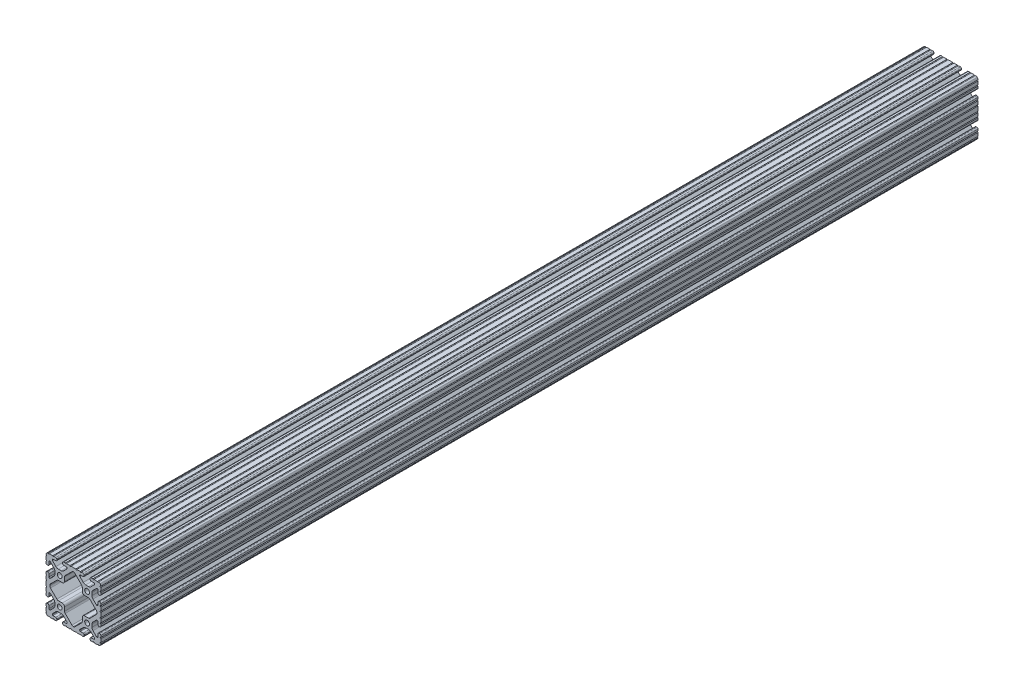
SolidWorks part; units mm, degrees
material "6061-T6 (SS)"
ref_plane "Front Plane" through (0, 0, 0) normal (0, 0, 1) x (1, 0, 0)
ref_plane "Top Plane" through (0, 0, 0) normal (0, 1, 0) x (1, 0, 0)
ref_plane "Right Plane" through (0, 0, 0) normal (1, 0, 0) x (0, 0, -1)
ref_plane "Plane1" through (0, 0, -609.6) normal (0, 0, -1) x (-1, 0, 0)
sketch "Sketch1" plane through (0, 0, -609.6) normal (0, 0, -1) x (-1, 0, 0)
  line L0 (31.9021, -2.4756) -> (23.0141, -11.3637)
  line L1 (20.769, -12.2936) -> (15.4686, -12.2936)
  line L2 (12.2936, -15.4686) -> (12.2936, -20.5983)
  line L3 (11.3637, -22.8433) -> (2.0515, -32.1555)
  line L4 (-2.0515, -32.1555) -> (-11.3637, -22.8433)
  line L5 (-12.2936, -20.5983) -> (-12.2936, -15.4686)
  line L6 (-15.4686, -12.2936) -> (-20.769, -12.2936)
  line L7 (-23.0141, -11.3637) -> (-31.9021, -2.4756)
  line L8 (-31.9021, 2.4756) -> (-23.0141, 11.3637)
  line L9 (-20.769, 12.2936) -> (-15.4686, 12.2936)
  line L10 (-12.2936, 15.4686) -> (-12.2936, 20.5983)
  line L11 (-11.3637, 22.8433) -> (-2.0515, 32.1555)
  line L12 (2.0515, 32.1555) -> (11.3637, 22.8433)
  line L13 (12.2936, 20.5983) -> (12.2936, 15.4686)
  line L14 (15.4686, 12.2936) -> (20.769, 12.2936)
  line L15 (23.0141, 11.3637) -> (31.9021, 2.4756)
  line L16 (36.5252, -23.0554) -> (35.6108, -23.0554)
  line L17 (34.036, -24.6302) -> (34.036, -28.448)
  line L18 (33.147, -29.337) -> (32.6643, -29.337)
  line L19 (32.0357, -29.0766) -> (27.1976, -24.2385)
  line L20 (25.8064, -20.8799) -> (25.8064, -17.2201)
  line L21 (27.1976, -13.8615) -> (31.9489, -9.1101)
  line L22 (32.7869, -8.763) -> (33.0603, -8.763)
  line L23 (34.036, -9.7387) -> (34.036, -13.4698)
  line L24 (35.6108, -15.0446) -> (36.5252, -15.0446)
  line L25 (38.1, -13.4698) -> (38.1, -11.075)
  line L26 (38.1, -9.552) -> (38.1, -4.7238)
  line L27 (38.1, -3.2007) -> (38.1, 3.2007)
  line L28 (38.1, 4.7238) -> (38.1, 9.552)
  line L29 (38.1, 11.075) -> (38.1, 13.4698)
  line L30 (36.5252, 15.0446) -> (35.6108, 15.0446)
  line L31 (34.036, 13.4698) -> (34.036, 9.7387)
  line L32 (33.0603, 8.763) -> (32.7869, 8.763)
  line L33 (31.9489, 9.1101) -> (27.1976, 13.8615)
  line L34 (25.8064, 17.2201) -> (25.8064, 20.8799)
  line L35 (27.1976, 24.2385) -> (32.0357, 29.0766)
  line L36 (32.6643, 29.337) -> (33.147, 29.337)
  line L37 (34.036, 28.448) -> (34.036, 24.6302)
  line L38 (35.6108, 23.0554) -> (36.5252, 23.0554)
  line L39 (38.1, 24.6302) -> (38.1, 27.0238)
  line L40 (38.1, 28.5453) -> (38.1, 33.373)
  line L41 (33.4288, 38.1) -> (28.6011, 38.1)
  line L42 (27.0772, 38.1) -> (24.6888, 38.1)
  line L43 (23.114, 36.5252) -> (23.114, 35.6108)
  line L44 (24.6888, 34.036) -> (28.448, 34.036)
  line L45 (29.337, 33.147) -> (29.337, 32.7207)
  line L46 (29.1002, 31.8885) -> (24.4093, 27.1976)
  line L47 (21.0507, 25.8064) -> (17.0493, 25.8064)
  line L48 (13.6907, 27.1976) -> (9.0234, 31.8649)
  line L49 (8.763, 32.4935) -> (8.763, 33.147)
  line L50 (9.652, 34.036) -> (13.4112, 34.036)
  line L51 (14.986, 35.6108) -> (14.986, 36.5252)
  line L52 (13.4112, 38.1) -> (11.1289, 38.1)
  line L53 (9.6053, 38.1) -> (4.7773, 38.1)
  line L54 (3.2537, 38.1) -> (-3.2537, 38.1)
  line L55 (-4.7773, 38.1) -> (-9.6053, 38.1)
  line L56 (-11.1289, 38.1) -> (-13.4112, 38.1)
  line L57 (-14.986, 36.5252) -> (-14.986, 35.6108)
  line L58 (-13.4112, 34.036) -> (-9.652, 34.036)
  line L59 (-8.763, 33.147) -> (-8.763, 32.4935)
  line L60 (-9.0234, 31.8649) -> (-13.6907, 27.1976)
  line L61 (-17.0493, 25.8064) -> (-21.0507, 25.8064)
  line L62 (-24.4093, 27.1976) -> (-29.1002, 31.8885)
  line L63 (-29.337, 32.7207) -> (-29.337, 33.147)
  line L64 (-28.448, 34.036) -> (-24.6888, 34.036)
  line L65 (-23.114, 35.6108) -> (-23.114, 36.5252)
  line L66 (-24.6888, 38.1) -> (-27.0772, 38.1)
  line L67 (-28.6011, 38.1) -> (-33.4288, 38.1)
  line L68 (-38.1, 33.373) -> (-38.1, 28.5453)
  line L69 (-38.1, 27.0238) -> (-38.1, 24.6302)
  line L70 (-36.5252, 23.0554) -> (-35.6108, 23.0554)
  line L71 (-34.036, 24.6302) -> (-34.036, 28.448)
  line L72 (-33.147, 29.337) -> (-32.6643, 29.337)
  line L73 (-32.0357, 29.0766) -> (-27.1976, 24.2385)
  line L74 (-25.8064, 20.8799) -> (-25.8064, 17.2201)
  line L75 (-27.1976, 13.8615) -> (-31.9489, 9.1101)
  line L76 (-32.7869, 8.763) -> (-33.0603, 8.763)
  line L77 (-34.036, 9.7387) -> (-34.036, 13.4698)
  line L78 (-35.6108, 15.0446) -> (-36.5252, 15.0446)
  line L79 (-38.1, 13.4698) -> (-38.1, 11.075)
  line L80 (-38.1, 9.552) -> (-38.1, 4.7238)
  line L81 (-38.1, 3.2007) -> (-38.1, -3.2007)
  line L82 (-38.1, -4.7238) -> (-38.1, -9.552)
  line L83 (-38.1, -11.075) -> (-38.1, -13.4698)
  line L84 (-36.5252, -15.0446) -> (-35.6108, -15.0446)
  line L85 (-34.036, -13.4698) -> (-34.036, -9.7387)
  line L86 (-33.0603, -8.763) -> (-32.7869, -8.763)
  line L87 (-31.9489, -9.1101) -> (-27.1976, -13.8615)
  line L88 (-25.8064, -17.2201) -> (-25.8064, -20.8799)
  line L89 (-27.1976, -24.2385) -> (-32.0357, -29.0766)
  line L90 (-32.6643, -29.337) -> (-33.147, -29.337)
  line L91 (-34.036, -28.448) -> (-34.036, -24.6302)
  line L92 (-35.6108, -23.0554) -> (-36.5252, -23.0554)
  line L93 (-38.1, -24.6302) -> (-38.1, -27.0238)
  line L94 (-38.1, -28.5453) -> (-38.1, -33.373)
  line L95 (-33.4288, -38.1) -> (-28.6011, -38.1)
  line L96 (-27.0772, -38.1) -> (-24.6888, -38.1)
  line L97 (-23.114, -36.5252) -> (-23.114, -35.6108)
  line L98 (-24.6888, -34.036) -> (-28.448, -34.036)
  line L99 (-29.337, -33.147) -> (-29.337, -32.7207)
  line L100 (-29.1002, -31.8885) -> (-24.4093, -27.1976)
  line L101 (-21.0507, -25.8064) -> (-17.0493, -25.8064)
  line L102 (-13.6907, -27.1976) -> (-9.0234, -31.8649)
  line L103 (-8.763, -32.4935) -> (-8.763, -33.147)
  line L104 (-9.652, -34.036) -> (-13.4112, -34.036)
  line L105 (-14.986, -35.6108) -> (-14.986, -36.5252)
  line L106 (-13.4112, -38.1) -> (-11.1289, -38.1)
  line L107 (-9.6053, -38.1) -> (-4.7773, -38.1)
  line L108 (-3.2537, -38.1) -> (3.2537, -38.1)
  line L109 (4.7773, -38.1) -> (9.6053, -38.1)
  line L110 (11.1289, -38.1) -> (13.4112, -38.1)
  line L111 (14.986, -36.5252) -> (14.986, -35.6108)
  line L112 (13.4112, -34.036) -> (9.652, -34.036)
  line L113 (8.763, -33.147) -> (8.763, -32.4935)
  line L114 (9.0234, -31.8649) -> (13.6907, -27.1976)
  line L115 (17.0493, -25.8064) -> (21.0507, -25.8064)
  line L116 (24.4093, -27.1976) -> (29.1002, -31.8885)
  line L117 (29.337, -32.7207) -> (29.337, -33.147)
  line L118 (28.448, -34.036) -> (24.6888, -34.036)
  line L119 (23.114, -35.6108) -> (23.114, -36.5252)
  line L120 (24.6888, -38.1) -> (27.0772, -38.1)
  line L121 (28.6011, -38.1) -> (33.4288, -38.1)
  line L122 (38.1, -33.373) -> (38.1, -28.5453)
  line L123 (38.1, -27.0238) -> (38.1, -24.6302)
  arc A0 (31.9021, 2.4756) -> (32.7287, 0) centre (29.8367, 0.4102) cw
  arc A1 (32.7287, 0) -> (31.9021, -2.4756) centre (29.8367, -0.4102) cw
  arc A2 (23.0141, -11.3637) -> (20.769, -12.2936) centre (20.769, -9.1186) cw
  arc A3 (15.4686, -12.2936) -> (12.2936, -15.4686) centre (15.4686, -15.4686) ccw
  arc A4 (12.2936, -20.5983) -> (11.3637, -22.8433) centre (9.1186, -20.5983) cw
  arc A5 (2.0515, -32.1555) -> (0, -33.011) centre (-0.0139, -30.09) cw
  arc A6 (0, -33.011) -> (-2.0515, -32.1555) centre (0.0139, -30.09) cw
  arc A7 (-11.3637, -22.8433) -> (-12.2936, -20.5983) centre (-9.1186, -20.5983) cw
  arc A8 (-12.2936, -15.4686) -> (-15.4686, -12.2936) centre (-15.4686, -15.4686) ccw
  arc A9 (-20.769, -12.2936) -> (-23.0141, -11.3637) centre (-20.769, -9.1186) cw
  arc A10 (-31.9021, -2.4756) -> (-32.7287, 0) centre (-29.8367, -0.4102) cw
  arc A11 (-32.7287, 0) -> (-31.9021, 2.4756) centre (-29.8367, 0.4102) cw
  arc A12 (-23.0141, 11.3637) -> (-20.769, 12.2936) centre (-20.769, 9.1186) cw
  arc A13 (-15.4686, 12.2936) -> (-12.2936, 15.4686) centre (-15.4686, 15.4686) ccw
  arc A14 (-12.2936, 20.5983) -> (-11.3637, 22.8433) centre (-9.1186, 20.5983) cw
  arc A15 (-2.0515, 32.1555) -> (0, 33.011) centre (0.0139, 30.09) cw
  arc A16 (0, 33.011) -> (2.0515, 32.1555) centre (-0.0139, 30.09) cw
  arc A17 (11.3637, 22.8433) -> (12.2936, 20.5983) centre (9.1186, 20.5983) cw
  arc A18 (12.2936, 15.4686) -> (15.4686, 12.2936) centre (15.4686, 15.4686) ccw
  arc A19 (20.769, 12.2936) -> (23.0141, 11.3637) centre (20.769, 9.1186) cw
  circle A20 centre (19.05, -19.05) radius 3.3274
  circle A21 centre (19.05, 19.05) radius 3.3274
  circle A22 centre (-19.05, 19.05) radius 3.3274
  circle A23 centre (-19.05, -19.05) radius 3.3274
  arc A24 (38.1, -24.6302) -> (36.5252, -23.0554) centre (36.5252, -24.6302) ccw
  arc A25 (35.6108, -23.0554) -> (34.036, -24.6302) centre (35.6108, -24.6302) ccw
  arc A26 (34.036, -28.448) -> (33.147, -29.337) centre (33.147, -28.448) cw
  arc A27 (32.6643, -29.337) -> (32.0357, -29.0766) centre (32.6643, -28.448) cw
  arc A28 (27.1976, -24.2385) -> (25.8064, -20.8799) centre (30.5562, -20.8799) cw
  arc A29 (25.8064, -17.2201) -> (27.1976, -13.8615) centre (30.5562, -17.2201) cw
  arc A30 (31.9489, -9.1101) -> (32.7869, -8.763) centre (32.7869, -9.9481) cw
  arc A31 (33.0603, -8.763) -> (34.036, -9.7387) centre (33.0603, -9.7387) cw
  arc A32 (34.036, -13.4698) -> (35.6108, -15.0446) centre (35.6108, -13.4698) ccw
  arc A33 (36.5252, -15.0446) -> (38.1, -13.4698) centre (36.5252, -13.4698) ccw
  arc A34 (38.1, -11.075) -> (38.1, -9.552) centre (37.9035, -10.3135) cw
  arc A35 (38.1, -4.7238) -> (38.1, -3.2007) centre (37.9035, -3.9622) cw
  arc A36 (38.1, 3.2007) -> (38.1, 4.7238) centre (37.9035, 3.9622) cw
  arc A37 (38.1, 9.552) -> (38.1, 11.075) centre (37.9035, 10.3135) cw
  arc A38 (38.1, 13.4698) -> (36.5252, 15.0446) centre (36.5252, 13.4698) ccw
  arc A39 (35.6108, 15.0446) -> (34.036, 13.4698) centre (35.6108, 13.4698) ccw
  arc A40 (34.036, 9.7387) -> (33.0603, 8.763) centre (33.0603, 9.7387) cw
  arc A41 (32.7869, 8.763) -> (31.9489, 9.1101) centre (32.7869, 9.9481) cw
  arc A42 (27.1976, 13.8615) -> (25.8064, 17.2201) centre (30.5562, 17.2201) cw
  arc A43 (25.8064, 20.8799) -> (27.1976, 24.2385) centre (30.5562, 20.8799) cw
  arc A44 (32.0357, 29.0766) -> (32.6643, 29.337) centre (32.6643, 28.448) cw
  arc A45 (33.147, 29.337) -> (34.036, 28.448) centre (33.147, 28.448) cw
  arc A46 (34.036, 24.6302) -> (35.6108, 23.0554) centre (35.6108, 24.6302) ccw
  arc A47 (36.5252, 23.0554) -> (38.1, 24.6302) centre (36.5252, 24.6302) ccw
  arc A48 (38.1, 27.0238) -> (38.1, 28.5453) centre (37.9035, 27.7845) cw
  arc A49 (38.1, 33.373) -> (38.1, 34.8455) centre (37.9035, 34.1092) cw
  arc A50 (38.1, 34.8455) -> (37.0861, 37.1826) centre (34.925, 34.8566) ccw
  arc A51 (37.0861, 37.1826) -> (34.9527, 38.1) centre (34.8521, 34.9266) ccw
  arc A52 (34.9527, 38.1) -> (33.4288, 38.1) centre (34.1907, 38.0824) cw
  arc A53 (28.6011, 38.1) -> (27.0772, 38.1) centre (27.8392, 38.0824) cw
  arc A54 (24.6888, 38.1) -> (23.114, 36.5252) centre (24.6888, 36.5252) ccw
  arc A55 (23.114, 35.6108) -> (24.6888, 34.036) centre (24.6888, 35.6108) ccw
  arc A56 (28.448, 34.036) -> (29.337, 33.147) centre (28.448, 33.147) cw
  arc A57 (29.337, 32.7207) -> (29.1002, 31.8885) centre (28.4716, 32.5172) cw
  arc A58 (24.4093, 27.1976) -> (21.0507, 25.8064) centre (21.0507, 30.5562) cw
  arc A59 (17.0493, 25.8064) -> (13.6907, 27.1976) centre (17.0493, 30.5562) cw
  arc A60 (9.0234, 31.8649) -> (8.763, 32.4935) centre (9.652, 32.4935) cw
  arc A61 (8.763, 33.147) -> (9.652, 34.036) centre (9.652, 33.147) cw
  arc A62 (13.4112, 34.036) -> (14.986, 35.6108) centre (13.4112, 35.6108) ccw
  arc A63 (14.986, 36.5252) -> (13.4112, 38.1) centre (13.4112, 36.5252) ccw
  arc A64 (11.1289, 38.1) -> (9.6053, 38.1) centre (10.3671, 38.0824) cw
  arc A65 (4.7773, 38.1) -> (3.2537, 38.1) centre (4.0155, 38.0824) cw
  arc A66 (-3.2537, 38.1) -> (-4.7773, 38.1) centre (-4.0155, 38.0824) cw
  arc A67 (-9.6053, 38.1) -> (-11.1289, 38.1) centre (-10.3671, 38.0824) cw
  arc A68 (-13.4112, 38.1) -> (-14.986, 36.5252) centre (-13.4112, 36.5252) ccw
  arc A69 (-14.986, 35.6108) -> (-13.4112, 34.036) centre (-13.4112, 35.6108) ccw
  arc A70 (-9.652, 34.036) -> (-8.763, 33.147) centre (-9.652, 33.147) cw
  arc A71 (-8.763, 32.4935) -> (-9.0234, 31.8649) centre (-9.652, 32.4935) cw
  arc A72 (-13.6907, 27.1976) -> (-17.0493, 25.8064) centre (-17.0493, 30.5562) cw
  arc A73 (-21.0507, 25.8064) -> (-24.4093, 27.1976) centre (-21.0507, 30.5562) cw
  arc A74 (-29.1002, 31.8885) -> (-29.337, 32.7207) centre (-28.4716, 32.5172) cw
  arc A75 (-29.337, 33.147) -> (-28.448, 34.036) centre (-28.448, 33.147) cw
  arc A76 (-24.6888, 34.036) -> (-23.114, 35.6108) centre (-24.6888, 35.6108) ccw
  arc A77 (-23.114, 36.5252) -> (-24.6888, 38.1) centre (-24.6888, 36.5252) ccw
  arc A78 (-27.0772, 38.1) -> (-28.6011, 38.1) centre (-27.8392, 38.0824) cw
  arc A79 (-33.4288, 38.1) -> (-34.9527, 38.1) centre (-34.1907, 38.0824) cw
  arc A80 (-34.9527, 38.1) -> (-37.0861, 37.1826) centre (-34.8521, 34.9266) ccw
  arc A81 (-37.0861, 37.1826) -> (-38.1, 34.8455) centre (-34.925, 34.8566) ccw
  arc A82 (-38.1, 34.8455) -> (-38.1, 33.373) centre (-37.9035, 34.1092) cw
  arc A83 (-38.1, 28.5453) -> (-38.1, 27.0238) centre (-37.9035, 27.7845) cw
  arc A84 (-38.1, 24.6302) -> (-36.5252, 23.0554) centre (-36.5252, 24.6302) ccw
  arc A85 (-35.6108, 23.0554) -> (-34.036, 24.6302) centre (-35.6108, 24.6302) ccw
  arc A86 (-34.036, 28.448) -> (-33.147, 29.337) centre (-33.147, 28.448) cw
  arc A87 (-32.6643, 29.337) -> (-32.0357, 29.0766) centre (-32.6643, 28.448) cw
  arc A88 (-27.1976, 24.2385) -> (-25.8064, 20.8799) centre (-30.5562, 20.8799) cw
  arc A89 (-25.8064, 17.2201) -> (-27.1976, 13.8615) centre (-30.5562, 17.2201) cw
  arc A90 (-31.9489, 9.1101) -> (-32.7869, 8.763) centre (-32.7869, 9.9481) cw
  arc A91 (-33.0603, 8.763) -> (-34.036, 9.7387) centre (-33.0603, 9.7387) cw
  arc A92 (-34.036, 13.4698) -> (-35.6108, 15.0446) centre (-35.6108, 13.4698) ccw
  arc A93 (-36.5252, 15.0446) -> (-38.1, 13.4698) centre (-36.5252, 13.4698) ccw
  arc A94 (-38.1, 11.075) -> (-38.1, 9.552) centre (-37.9035, 10.3135) cw
  arc A95 (-38.1, 4.7238) -> (-38.1, 3.2007) centre (-37.9035, 3.9622) cw
  arc A96 (-38.1, -3.2007) -> (-38.1, -4.7238) centre (-37.9035, -3.9622) cw
  arc A97 (-38.1, -9.552) -> (-38.1, -11.075) centre (-37.9035, -10.3135) cw
  arc A98 (-38.1, -13.4698) -> (-36.5252, -15.0446) centre (-36.5252, -13.4698) ccw
  arc A99 (-35.6108, -15.0446) -> (-34.036, -13.4698) centre (-35.6108, -13.4698) ccw
  arc A100 (-34.036, -9.7387) -> (-33.0603, -8.763) centre (-33.0603, -9.7387) cw
  arc A101 (-32.7869, -8.763) -> (-31.9489, -9.1101) centre (-32.7869, -9.9481) cw
  arc A102 (-27.1976, -13.8615) -> (-25.8064, -17.2201) centre (-30.5562, -17.2201) cw
  arc A103 (-25.8064, -20.8799) -> (-27.1976, -24.2385) centre (-30.5562, -20.8799) cw
  arc A104 (-32.0357, -29.0766) -> (-32.6643, -29.337) centre (-32.6643, -28.448) cw
  arc A105 (-33.147, -29.337) -> (-34.036, -28.448) centre (-33.147, -28.448) cw
  arc A106 (-34.036, -24.6302) -> (-35.6108, -23.0554) centre (-35.6108, -24.6302) ccw
  arc A107 (-36.5252, -23.0554) -> (-38.1, -24.6302) centre (-36.5252, -24.6302) ccw
  arc A108 (-38.1, -27.0238) -> (-38.1, -28.5453) centre (-37.9035, -27.7845) cw
  arc A109 (-38.1, -33.373) -> (-38.1, -34.8455) centre (-37.9035, -34.1092) cw
  arc A110 (-38.1, -34.8455) -> (-37.0861, -37.1826) centre (-34.925, -34.8566) ccw
  arc A111 (-37.0861, -37.1826) -> (-34.9527, -38.1) centre (-34.8521, -34.9266) ccw
  arc A112 (-34.9527, -38.1) -> (-33.4288, -38.1) centre (-34.1907, -38.0824) cw
  arc A113 (-28.6011, -38.1) -> (-27.0772, -38.1) centre (-27.8392, -38.0824) cw
  arc A114 (-24.6888, -38.1) -> (-23.114, -36.5252) centre (-24.6888, -36.5252) ccw
  arc A115 (-23.114, -35.6108) -> (-24.6888, -34.036) centre (-24.6888, -35.6108) ccw
  arc A116 (-28.448, -34.036) -> (-29.337, -33.147) centre (-28.448, -33.147) cw
  arc A117 (-29.337, -32.7207) -> (-29.1002, -31.8885) centre (-28.4716, -32.5172) cw
  arc A118 (-24.4093, -27.1976) -> (-21.0507, -25.8064) centre (-21.0507, -30.5562) cw
  arc A119 (-17.0493, -25.8064) -> (-13.6907, -27.1976) centre (-17.0493, -30.5562) cw
  arc A120 (-9.0234, -31.8649) -> (-8.763, -32.4935) centre (-9.652, -32.4935) cw
  arc A121 (-8.763, -33.147) -> (-9.652, -34.036) centre (-9.652, -33.147) cw
  arc A122 (-13.4112, -34.036) -> (-14.986, -35.6108) centre (-13.4112, -35.6108) ccw
  arc A123 (-14.986, -36.5252) -> (-13.4112, -38.1) centre (-13.4112, -36.5252) ccw
  arc A124 (-11.1289, -38.1) -> (-9.6053, -38.1) centre (-10.3671, -38.0824) cw
  arc A125 (-4.7773, -38.1) -> (-3.2537, -38.1) centre (-4.0155, -38.0824) cw
  arc A126 (3.2537, -38.1) -> (4.7773, -38.1) centre (4.0155, -38.0824) cw
  arc A127 (9.6053, -38.1) -> (11.1289, -38.1) centre (10.3671, -38.0824) cw
  arc A128 (13.4112, -38.1) -> (14.986, -36.5252) centre (13.4112, -36.5252) ccw
  arc A129 (14.986, -35.6108) -> (13.4112, -34.036) centre (13.4112, -35.6108) ccw
  arc A130 (9.652, -34.036) -> (8.763, -33.147) centre (9.652, -33.147) cw
  arc A131 (8.763, -32.4935) -> (9.0234, -31.8649) centre (9.652, -32.4935) cw
  arc A132 (13.6907, -27.1976) -> (17.0493, -25.8064) centre (17.0493, -30.5562) cw
  arc A133 (21.0507, -25.8064) -> (24.4093, -27.1976) centre (21.0507, -30.5562) cw
  arc A134 (29.1002, -31.8885) -> (29.337, -32.7207) centre (28.4716, -32.5172) cw
  arc A135 (29.337, -33.147) -> (28.448, -34.036) centre (28.448, -33.147) cw
  arc A136 (24.6888, -34.036) -> (23.114, -35.6108) centre (24.6888, -35.6108) ccw
  arc A137 (23.114, -36.5252) -> (24.6888, -38.1) centre (24.6888, -36.5252) ccw
  arc A138 (27.0772, -38.1) -> (28.6011, -38.1) centre (27.8392, -38.0824) cw
  arc A139 (33.4288, -38.1) -> (34.9527, -38.1) centre (34.1907, -38.0824) cw
  arc A140 (34.9527, -38.1) -> (37.0861, -37.1826) centre (34.8521, -34.9266) ccw
  arc A141 (37.0861, -37.1826) -> (38.1, -34.8455) centre (34.925, -34.8566) ccw
  arc A142 (38.1, -34.8455) -> (38.1, -33.373) centre (37.9035, -34.1092) cw
  arc A143 (38.1, -28.5453) -> (38.1, -27.0238) centre (37.9035, -27.7845) cw
extrude "Boss-Extrude1" add sketch "Sketch1" against normal blind 1219.2
